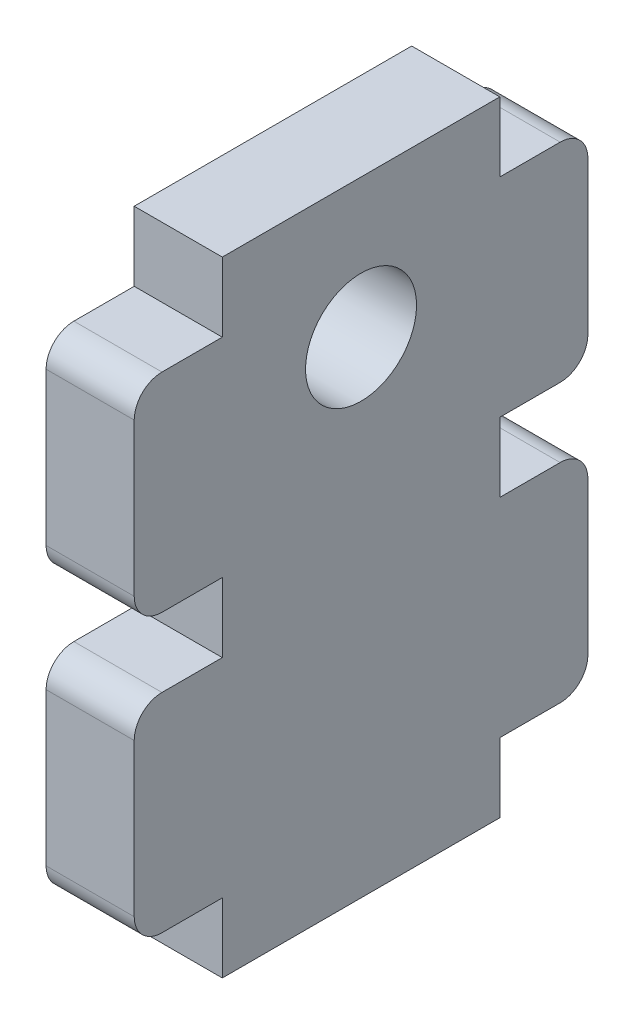
SolidWorks part; units mm, degrees
ref_plane "Front Plane" through (0, 0, 0) normal (0, 0, 1) x (1, 0, 0)
ref_plane "Top Plane" through (0, 0, 0) normal (0, 1, 0) x (1, 0, 0)
ref_plane "Right Plane" through (0, 0, 0) normal (1, 0, 0) x (0, 0, -1)
sketch "Sketch1" plane through (0, 0, 0) normal (1, 0, 0) x (0, 0, -1)
  line L0 (0, 40) -> (0, 45)
  line L1 (0, 0) -> (20, 0)
  line L2 (0, 0) -> (0, 5)
  line L3 (0, 45) -> (20, 45)
  line L4 (20, 0) -> (20, 5)
  line L5 (0, 5) -> (-6.35, 5)
  line L7 (0, 20) -> (-6.35, 20)
  line L8 (-6.35, 5) -> (-6.35, 20)
  line L9 (0, 40) -> (-6.35, 40)
  line L11 (0, 25) -> (-6.35, 25)
  line L12 (-6.35, 40) -> (-6.35, 25)
  line L13 (20, 40) -> (26.35, 40)
  line L15 (20, 25) -> (26.35, 25)
  line L16 (26.35, 40) -> (26.35, 25)
  line L17 (20, 20) -> (26.35, 20)
  line L19 (20, 5) -> (26.35, 5)
  line L20 (26.35, 20) -> (26.35, 5)
  line L21 (0, 20) -> (0, 25)
  line L22 (20, 40) -> (20, 45)
  line L23 (20, 20) -> (20, 25)
  dimension "D1" = 20
  dimension "D2" = 45
  dimension "D3" = 5
  dimension "D4" = 15
  dimension "D5" = 6.35
  dimension "D6" = 6.35
  dimension "D7" = 15
  dimension "D8" = 5
  dimension "D9" = 5
  dimension "D10" = 15
  dimension "D11" = 6.35
  dimension "D12" = 15
  dimension "D13" = 6.35
  dimension "D14" = 5
extrude "Boss-Extrude1" add sketch "Sketch1" along normal blind 6.35
fillet "Fillet1" radius 2 8 edges at (3.175, 5, -26.35) (3.175, 20, -26.35) (3.175, 25, -26.35) (3.175, 40, -26.35) (3.175, 5, 6.35) (3.175, 20, 6.35) (3.175, 25, 6.35) (3.175, 40, 6.35)
sketch "Sketch2" plane through (6.35, 0, 0) normal (1, 0, 0) x (0, 0, -1)
  line L1 (0, 45) -> (20, 45) construction
  line L2 (0, 45) -> (0, 25) construction
  line L3 (0, 25) -> (20, 25) construction
  line L4 (20, 45) -> (20, 25) construction
  circle A0 centre (10, 35) radius 4
  point P7 (0, 0)
  point P8 (0, 0)
  point P9 (10, 25)
  point P10 (0, 35)
  dimension "D3" = 8
  dimension "D1" = 20
  dimension "D2" = 20
extrude "Cut-Extrude1" cut sketch "Sketch2" against normal through all
